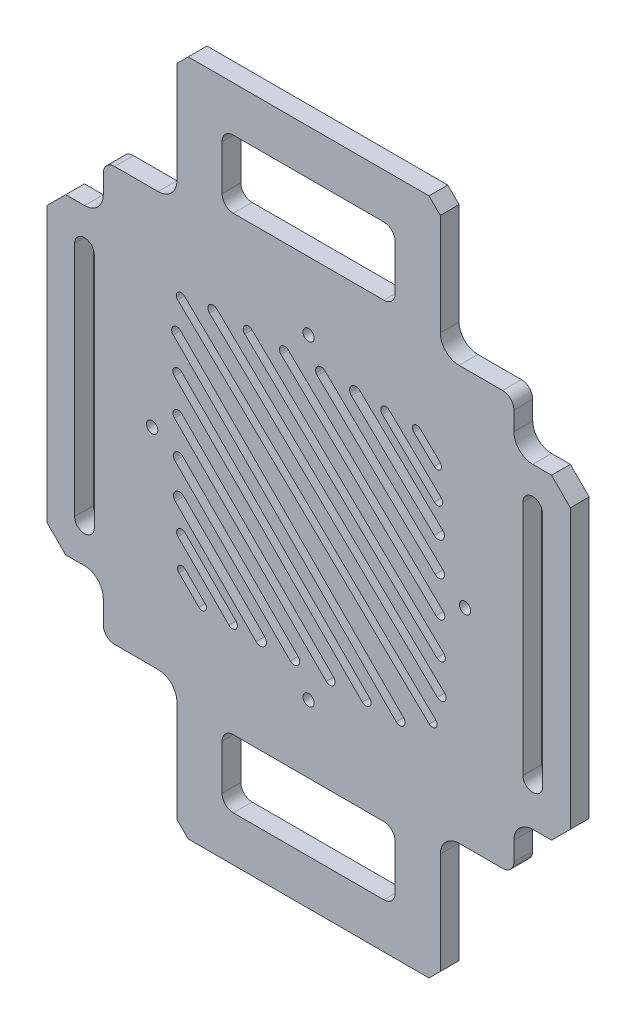
SolidWorks part; units mm, degrees
ref_plane "Front Plane" through (0, 0, 0) normal (0, 0, 1) x (1, 0, 0)
ref_plane "Top Plane" through (0, 0, 0) normal (0, 1, 0) x (1, 0, 0)
ref_plane "Right Plane" through (0, 0, 0) normal (1, 0, 0) x (0, 0, -1)
sketch "Sketch1" plane through (0, 0, 0) normal (0, 0, 1) x (1, 0, 0)
  line L0 (-15, 92) -> (-10, 97)
  line L1 (54.5664, 110) -> (54.5664, 0) construction
  line L2 (3, 0) -> (14.5664, 0)
  line L3 (0, 3) -> (0, 9.1034)
  line L4 (3, 110) -> (14.5664, 110)
  line L5 (109.1327, 3) -> (109.1327, 8)
  line L6 (109.1327, 55) -> (0, 55) construction
  line L7 (-5, 97) -> (-10, 97)
  line L8 (-15, 19.1034) -> (-15, 92)
  line L9 (-10, 14.1034) -> (-5, 14.1034)
  line L10 (114.1327, 97) -> (119.1327, 97)
  line L11 (124.1327, 18) -> (124.1327, 92)
  line L12 (119.1327, 13) -> (114.1327, 13)
  line L13 (-10, 14.1034) -> (-15, 19.1034)
  line L14 (119.1327, 97) -> (124.1327, 92)
  line L15 (124.1327, 18) -> (119.1327, 13)
  line L16 (19.5664, 115) -> (19.5664, 142)
  line L17 (22.5664, 145) -> (86.5664, 145)
  line L18 (89.5664, 142) -> (89.5664, 115)
  line L19 (19.5664, -5) -> (19.5664, -32)
  line L20 (22.5664, -35) -> (86.5664, -35)
  line L21 (89.5664, -32) -> (89.5664, -5)
  line L22 (19.5664, 142) -> (22.5664, 145)
  line L23 (86.5664, 145) -> (89.5664, 142)
  line L24 (19.5664, -32) -> (22.5664, -35)
  line L25 (86.5664, -35) -> (89.5664, -32)
  line L26 (0, 102) -> (0, 107)
  line L27 (94.5664, 0) -> (106.1327, 0)
  line L28 (109.1327, 102) -> (109.1327, 107)
  line L29 (94.5664, 110) -> (106.1327, 110)
  line L30 (-5, 24.1034) -> (-5, 87) construction
  line L31 (34.5664, 133) -> (74.5664, 133)
  line L32 (31.5664, 130) -> (31.5664, 118)
  line L33 (34.5664, 115) -> (74.5664, 115)
  line L34 (77.5664, 130) -> (77.5664, 118)
  line L35 (34.5664, -23) -> (74.5664, -23)
  line L36 (31.5664, -20) -> (31.5664, -8)
  line L37 (34.5664, -5) -> (74.5664, -5)
  line L38 (77.5664, -20) -> (77.5664, -8)
  line L39 (-7.61, 24.1034) -> (-7.61, 87)
  line L40 (-2.39, 24.1034) -> (-2.39, 87)
  line L41 (114.1327, 24.1034) -> (114.1327, 87) construction
  line L42 (116.7428, 24.1034) -> (116.7428, 87)
  line L43 (111.5227, 24.1034) -> (111.5227, 87)
  line L44 (20.6622, 88.5645) -> (87.4833, 24.405) construction
  line L45 (21.5299, 89.4681) -> (88.351, 25.3087)
  line L46 (19.7945, 87.6608) -> (86.6156, 23.5013)
  line L47 (29.1888, 89.8374) -> (89.7343, 31.7036) construction
  line L48 (30.142, 90.8302) -> (90.6875, 32.6963)
  line L49 (28.2355, 88.8447) -> (88.7811, 30.7108)
  line L50 (38.5432, 89.7078) -> (89.563, 40.7203) construction
  line L51 (39.4833, 90.6869) -> (90.503, 41.6993)
  line L52 (37.6032, 88.7288) -> (88.6229, 39.7412)
  line L53 (48.1935, 89.8374) -> (89.3812, 50.2904) construction
  line L54 (49.154, 90.8377) -> (90.3416, 51.2907)
  line L55 (47.2331, 88.8372) -> (88.4207, 49.2901)
  line L56 (57.9019, 89.8374) -> (89.2008, 59.7852) construction
  line L57 (58.9133, 90.8908) -> (90.2122, 60.8386)
  line L58 (56.8905, 88.7841) -> (88.1894, 58.7319)
  line L59 (67.0872, 89.8374) -> (89.0301, 68.7685) construction
  line L60 (68.2008, 90.9973) -> (90.1438, 69.9284)
  line L61 (65.9735, 88.6776) -> (87.9165, 67.6087)
  line L62 (75.0728, 89.4681) -> (88.8889, 76.2023) construction
  line L63 (75.9856, 90.4189) -> (89.8018, 77.1531)
  line L64 (74.1599, 88.5174) -> (87.976, 75.2516)
  line L65 (83.3501, 89.4681) -> (88.7382, 84.2947) construction
  line L66 (84.1647, 90.3165) -> (89.5528, 85.1431)
  line L67 (82.5356, 88.6198) -> (87.9236, 83.4463)
  line L68 (20.6622, 88.5645) -> (87.4833, 24.405) construction
  line L69 (20.6622, 88.5645) -> (18.2773, 90.9045) construction
  line L70 (20.9494, 25.8707) -> (26.2243, 20.5819) construction
  line L71 (20.1167, 25.0402) -> (25.3916, 19.7513)
  line L72 (21.7822, 26.7012) -> (27.057, 21.4124)
  line L73 (20.7922, 34.1466) -> (34.3181, 20.5849) construction
  line L74 (19.859, 33.2158) -> (33.3848, 19.6541)
  line L75 (21.7254, 35.0773) -> (35.2513, 21.5157)
  line L76 (20.2713, 42.1237) -> (41.7532, 20.5849) construction
  line L77 (19.1328, 40.9882) -> (40.6147, 19.4494)
  line L78 (21.4098, 43.2592) -> (42.8917, 21.7204)
  line L79 (20.0968, 51.3074) -> (50.7381, 20.5849) construction
  line L80 (19.0629, 50.2761) -> (49.7042, 19.5537)
  line L81 (21.1308, 52.3386) -> (51.7721, 21.6161)
  line L82 (19.9124, 61.0139) -> (60.2347, 20.5849) construction
  line L83 (18.9306, 60.0347) -> (59.2528, 19.6056)
  line L84 (20.8943, 61.9932) -> (61.2165, 21.5642)
  line L85 (19.8587, 70.665) -> (69.8065, 20.5849) construction
  line L86 (18.8977, 69.7065) -> (68.8455, 19.6264)
  line L87 (20.8197, 71.6235) -> (70.7675, 21.5434)
  line L88 (19.5514, 80.0153) -> (78.8249, 20.5849) construction
  line L89 (18.577, 79.0434) -> (77.8504, 19.613)
  line L90 (20.5259, 80.9872) -> (79.7993, 21.5568)
  arc A0 (3, 0) -> (0, 3) centre (3, 3) cw
  arc A1 (106.1327, 0) -> (109.1327, 3) centre (106.1327, 3) ccw
  arc A2 (106.1327, 110) -> (109.1327, 107) centre (106.1327, 107) cw
  arc A3 (0, 107) -> (3, 110) centre (3, 107) cw
  circle A4 centre (54.5664, 97) radius 1.5
  circle A5 centre (54.5664, 13) radius 1.5
  circle A6 centre (96.1327, 55) radius 1.5
  circle A7 centre (13, 55) radius 1.5
  arc A8 (-5, 14.1034) -> (0, 9.1034) centre (-5, 9.1034) cw
  arc A9 (114.1327, 13) -> (109.1327, 8) centre (114.1327, 8) ccw
  arc A10 (114.1327, 97) -> (109.1327, 102) centre (114.1327, 102) cw
  arc A11 (-5, 97) -> (0, 102) centre (-5, 102) ccw
  arc A12 (19.5664, -5) -> (14.5664, 0) centre (14.5664, -5) ccw
  arc A13 (89.5664, -5) -> (94.5664, 0) centre (94.5664, -5) cw
  arc A14 (89.5664, 115) -> (94.5664, 110) centre (94.5664, 115) ccw
  arc A15 (19.5664, 115) -> (14.5664, 110) centre (14.5664, 115) cw
  arc A16 (34.5664, -23) -> (31.5664, -20) centre (34.5664, -20) cw
  arc A17 (74.5664, -23) -> (77.5664, -20) centre (74.5664, -20) ccw
  arc A18 (74.5664, -5) -> (77.5664, -8) centre (74.5664, -8) cw
  arc A19 (31.5664, -8) -> (34.5664, -5) centre (34.5664, -8) cw
  arc A20 (31.5664, 118) -> (34.5664, 115) centre (34.5664, 118) ccw
  arc A21 (74.5664, 115) -> (77.5664, 118) centre (74.5664, 118) ccw
  arc A22 (77.5664, 130) -> (74.5664, 133) centre (74.5664, 130) ccw
  arc A23 (34.5664, 133) -> (31.5664, 130) centre (34.5664, 130) ccw
  arc A24 (-7.61, 24.1034) -> (-2.39, 24.1034) centre (-5, 24.1034) ccw
  arc A25 (-2.39, 87) -> (-7.61, 87) centre (-5, 87) ccw
  arc A26 (116.7428, 24.1034) -> (111.5227, 24.1034) centre (114.1327, 24.1034) cw
  arc A27 (111.5227, 87) -> (116.7428, 87) centre (114.1327, 87) cw
  arc A28 (21.5299, 89.4681) -> (19.7945, 87.6608) centre (20.6622, 88.5645) ccw
  arc A29 (86.6156, 23.5013) -> (88.351, 25.3087) centre (87.4833, 24.405) ccw
  arc A30 (30.142, 90.8302) -> (28.2355, 88.8447) centre (29.1888, 89.8374) ccw
  arc A31 (88.7811, 30.7108) -> (90.6875, 32.6963) centre (89.7343, 31.7036) ccw
  arc A32 (39.4833, 90.6869) -> (37.6032, 88.7288) centre (38.5432, 89.7078) ccw
  arc A33 (88.6229, 39.7412) -> (90.503, 41.6993) centre (89.563, 40.7203) ccw
  arc A34 (49.154, 90.8377) -> (47.2331, 88.8372) centre (48.1935, 89.8374) ccw
  arc A35 (88.4207, 49.2901) -> (90.3416, 51.2907) centre (89.3812, 50.2904) ccw
  arc A36 (58.9133, 90.8908) -> (56.8905, 88.7841) centre (57.9019, 89.8374) ccw
  arc A37 (88.1894, 58.7319) -> (90.2122, 60.8386) centre (89.2008, 59.7852) ccw
  arc A38 (68.2008, 90.9973) -> (65.9735, 88.6776) centre (67.0872, 89.8374) ccw
  arc A39 (87.9165, 67.6087) -> (90.1438, 69.9284) centre (89.0301, 68.7685) ccw
  arc A40 (75.9856, 90.4189) -> (74.1599, 88.5174) centre (75.0728, 89.4681) ccw
  arc A41 (87.976, 75.2516) -> (89.8018, 77.1531) centre (88.8889, 76.2023) ccw
  arc A42 (84.1647, 90.3165) -> (82.5356, 88.6198) centre (83.3501, 89.4681) ccw
  arc A43 (87.9236, 83.4463) -> (89.5528, 85.1431) centre (88.7382, 84.2947) ccw
  arc A44 (20.1167, 25.0402) -> (21.7822, 26.7012) centre (20.9494, 25.8707) cw
  arc A45 (27.057, 21.4124) -> (25.3916, 19.7513) centre (26.2243, 20.5819) cw
  arc A46 (19.859, 33.2158) -> (21.7254, 35.0773) centre (20.7922, 34.1466) cw
  arc A47 (35.2513, 21.5157) -> (33.3848, 19.6541) centre (34.3181, 20.5849) cw
  arc A48 (19.1328, 40.9882) -> (21.4098, 43.2592) centre (20.2713, 42.1237) cw
  arc A49 (42.8917, 21.7204) -> (40.6147, 19.4494) centre (41.7532, 20.5849) cw
  arc A50 (19.0629, 50.2761) -> (21.1308, 52.3386) centre (20.0968, 51.3074) cw
  arc A51 (51.7721, 21.6161) -> (49.7042, 19.5537) centre (50.7381, 20.5849) cw
  arc A52 (18.9306, 60.0347) -> (20.8943, 61.9932) centre (19.9124, 61.0139) cw
  arc A53 (61.2165, 21.5642) -> (59.2528, 19.6056) centre (60.2347, 20.5849) cw
  arc A54 (18.8977, 69.7065) -> (20.8197, 71.6235) centre (19.8587, 70.665) cw
  arc A55 (70.7675, 21.5434) -> (68.8455, 19.6264) centre (69.8065, 20.5849) cw
  arc A56 (18.577, 79.0434) -> (20.5259, 80.9872) centre (19.5514, 80.0153) cw
  arc A57 (79.7993, 21.5568) -> (77.8504, 19.613) centre (78.8249, 20.5849) cw
  point P7 (0, 0)
  point P27 (-15, 97)
  point P28 (-15, 14.1034)
  point P31 (124.1327, 97)
  point P32 (124.1327, 13)
  point P43 (19.5664, 145)
  point P45 (89.5664, 145)
  point P47 (19.5664, -35)
  point P48 (89.5664, -35)
  point P64 (109.1327, 97)
  point P67 (0, 97)
  point P70 (19.5664, 0)
  point P73 (89.5664, 0)
  point P76 (89.5664, 110)
  point P79 (19.5664, 110)
  point P106 (-5, 55.5517)
  point P113 (114.1327, 55.5517)
  point P120 (54.0728, 56.4847)
  point P125 (59.4615, 60.7705)
  point P132 (64.0531, 65.214)
  point P139 (68.7874, 70.0639)
  point P146 (73.5513, 74.8113)
  point P153 (78.0587, 79.303)
  point P160 (81.9808, 82.8352)
  point P167 (86.0442, 86.8814)
  point P179 (23.5869, 23.2263)
  point P186 (27.5551, 27.3657)
  point P193 (31.0123, 31.3543)
  point P200 (35.4175, 35.9461)
  point P207 (40.0735, 40.7994)
  point P214 (44.8326, 45.625)
  point P221 (49.1881, 50.3001)
  dimension "D1" = 3
  dimension "D2" = 13
  dimension "D3" = 13
  dimension "D5" = 13
  dimension "D18" = 5
  dimension "D19" = 5
  dimension "D32" = 3
  dimension "D4" = 13
  dimension "D6" = 15
  dimension "D7" = 15
  dimension "D8" = 35
  dimension "D9" = 35
  dimension "D10" = 35
  dimension "D15" = 35
  dimension "D16" = 35
  dimension "D17" = 35
  dimension "D24" = 12
  dimension "D25" = 12
  dimension "D26" = 12
  dimension "D27" = 12
  dimension "D28" = 12
  dimension "D29" = 12
  dimension "D30" = 5
  dimension "D31" = 5
  dimension "D33" = 10
  dimension "D34" = 10
extrude "Boss-Extrude1" add sketch "Sketch1" along normal blind 5
